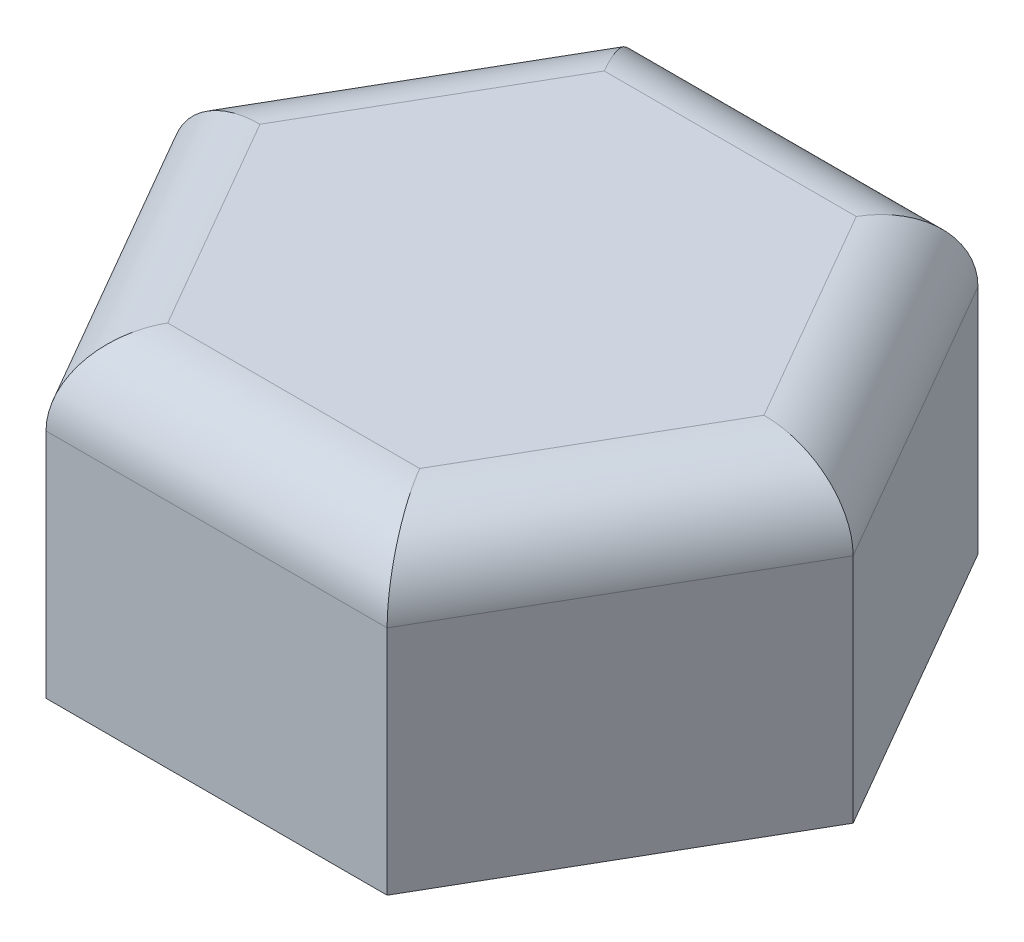
SolidWorks part; units mm, degrees
ref_plane "Front Plane" through (0, 0, 0) normal (0, 0, 1) x (1, 0, 0)
ref_plane "Top Plane" through (0, 0, 0) normal (0, 1, 0) x (1, 0, 0)
ref_plane "Right Plane" through (0, 0, 0) normal (1, 0, 0) x (0, 0, -1)
sketch "Sketch1" plane through (0, 0, 0) normal (0, 1, 0) x (1, 0, 0)
  line L1 (-4.42, 0) -> (-2.21, -3.8278)
  line L2 (-2.21, -3.8278) -> (2.21, -3.8278)
  line L3 (2.21, -3.8278) -> (4.42, 0)
  line L4 (4.42, 0) -> (2.21, 3.8278)
  line L5 (2.21, 3.8278) -> (-2.21, 3.8278)
  line L6 (-2.21, 3.8278) -> (-4.42, 0)
  circle A0 centre (0, 0) radius 3.8278 construction
  circle A1 centre (0, 0) radius 2.4
extrude "Boss-Extrude1" add sketch "Sketch1" along normal blind 4
fillet "Fillet1" radius 1 6 edges at (-3.315, 4, -1.9139) (0, 4, -3.8278) (3.315, 4, -1.9139) (3.315, 4, 1.9139) (0, 4, 3.8278) (-3.315, 4, 1.9139)
sketch "Sketch2" plane through (0, 4, 0) normal (0, 1, 0) x (1, 0, 0)
  circle A0 centre (0, 0) radius 2.4 construction
  circle A1 centre (0, 0) radius 2.4
extrude "Boss-Extrude4" add sketch "Sketch2" against normal blind 3
